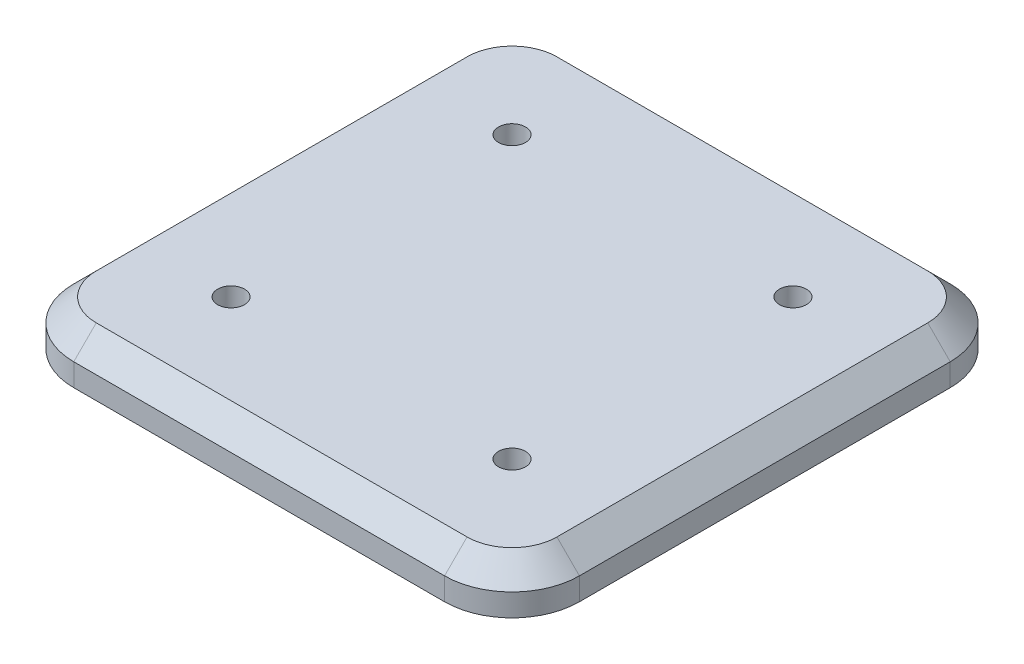
SolidWorks part; units mm, degrees
ref_plane "Front Plane" through (0, 0, 0) normal (0, 0, 1) x (1, 0, 0)
ref_plane "Top Plane" through (0, 0, 0) normal (0, 1, 0) x (1, 0, 0)
ref_plane "Right Plane" through (0, 0, 0) normal (1, 0, 0) x (0, 0, -1)
sketch "Sketch1" plane through (0, 0, 0) normal (0, 1, 0) x (1, 0, 0)
  line L0 (-82.5, 112.5) -> (82.5, 112.5)
  line L1 (112.5, 82.5) -> (112.5, -82.5)
  line L2 (82.5, -112.5) -> (-82.5, -112.5)
  line L3 (-112.5, -82.5) -> (-112.5, 82.5)
  arc A0 (-82.5, -112.5) -> (-112.5, -82.5) centre (-82.5, -82.5) cw
  arc A1 (112.5, -82.5) -> (82.5, -112.5) centre (82.5, -82.5) cw
  arc A2 (82.5, 112.5) -> (112.5, 82.5) centre (82.5, 82.5) cw
  arc A3 (-82.5, 112.5) -> (-112.5, 82.5) centre (-82.5, 82.5) ccw
  point P4 (0, 112.5)
  point P5 (-112.5, 0)
  point P13 (112.5, 112.5)
  point P16 (-112.5, 112.5)
  dimension "D2" = 30
  dimension "D1" = 225
extrude "Boss-Extrude1" add sketch "Sketch1" along normal mid plane 20
chamfer "Chamfer1" distance 10 angle 45 8 edges at (-112.5, 10, 0) (-103.7132, 10, -103.7132) (0, 10, -112.5) (103.7132, 10, -103.7132) (112.5, 10, 0) (103.7132, 10, 103.7132) (0, 10, 112.5) (-103.7132, 10, 103.7132)
sketch "Sketch2" plane through (0, 10, 0) normal (0, 1, 0) x (1, 0, 0)
  line L0 (62.5, 112.5) -> (62.5, -112.5) construction
  line L3 (-82.5, 112.5) -> (82.5, 112.5) construction
  line L4 (82.5, -112.5) -> (-82.5, -112.5) construction
  line L5 (-112.5, -82.5) -> (-112.5, 82.5) construction
  line L6 (-112.5, 62.5) -> (112.5, 62.5) construction
  line L7 (112.5, 82.5) -> (112.5, -82.5) construction
  line L8 (-148.0334, 0) -> (112.5, 0) construction
  line L9 (0, 112.5) -> (0, -112.5) construction
  circle A0 centre (62.5, 62.5) radius 6
  circle A1 centre (-62.5, 62.5) radius 6
  circle A2 centre (62.5, -62.5) radius 6
  circle A3 centre (-62.5, -62.5) radius 6
  dimension "D1" = 50
  dimension "D2" = 50
extrude "Cut-Extrude1" cut sketch "Sketch2" against normal offset from surface (10 mm away) 10 up to face at (0, 10, 0)
sketch "Sketch3" plane through (0, -10, 0) normal (0, -1, 0) x (1, 0, 0)
  line L0 (87.5, 112.5) -> (87.5, -112.5) construction
  line L1 (-82.5, 112.5) -> (82.5, 112.5) construction
  line L2 (82.5, -112.5) -> (-82.5, -112.5) construction
  line L3 (-112.5, 87.5) -> (112.5, 87.5) construction
  line L4 (-112.5, -82.5) -> (-112.5, 82.5) construction
  line L5 (112.5, 82.5) -> (112.5, -82.5) construction
  line L6 (0, 112.5) -> (0, -112.5) construction
  line L7 (-112.5, 0) -> (112.5, 0) construction
  circle A0 centre (87.5, 87.5) radius 6
  circle A1 centre (-87.5, 87.5) radius 6
  circle A2 centre (87.5, -87.5) radius 6
  circle A3 centre (-87.5, -87.5) radius 6
  dimension "D1" = 25
  dimension "D2" = 25
extrude "Cut-Extrude2" cut sketch "Sketch3" against normal offset from surface (10 mm away) 10 up to face at (0, -10, 0)
